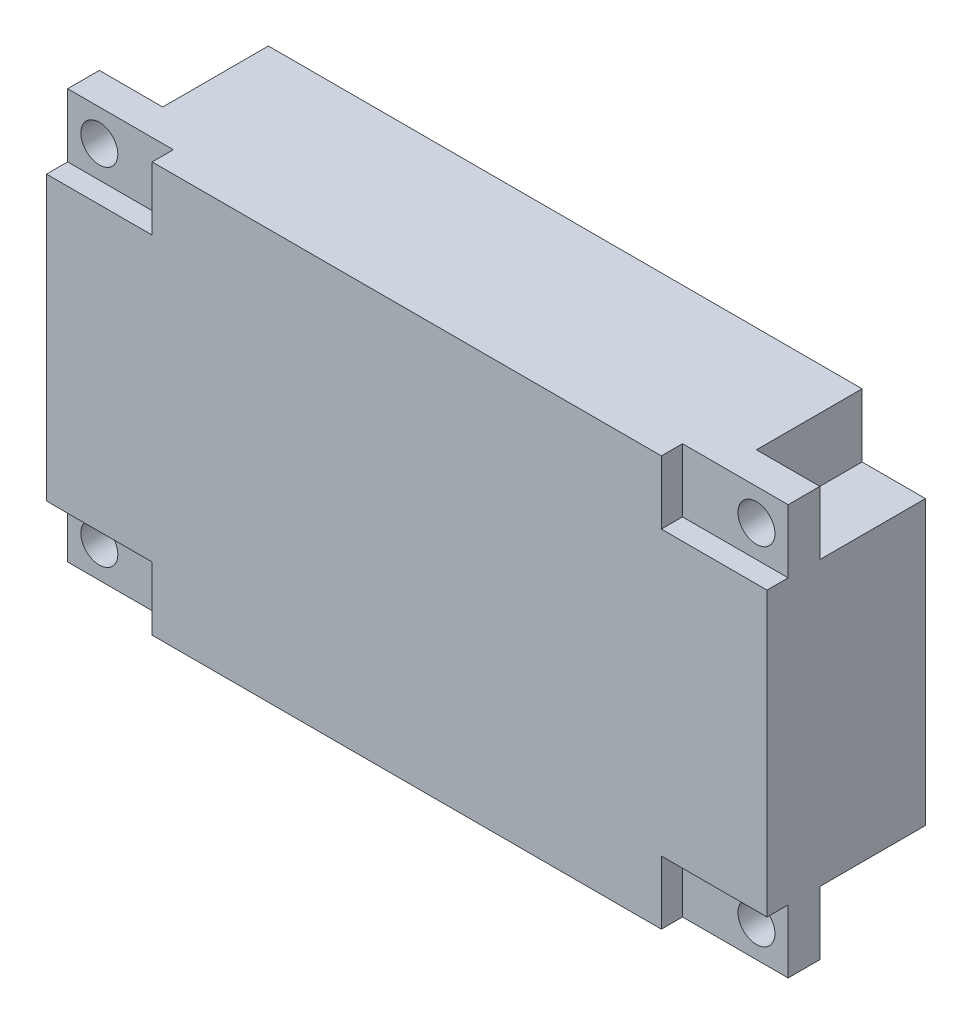
SolidWorks part; units mm, degrees
ref_plane "Plan de face" through (0, 0, 0) normal (0, 0, 1) x (1, 0, 0)
ref_plane "Plan de dessus" through (0, 0, 0) normal (0, 1, 0) x (1, 0, 0)
ref_plane "Plan de droite" through (0, 0, 0) normal (1, 0, 0) x (0, 0, -1)
sketch "Esquisse1" plane through (0, 0, 0) normal (0, 0, 1) x (1, 0, 0)
  line L1 (0, 0) -> (68.2, 0)
  line L2 (0, 0) -> (0, 38.8)
  line L3 (0, 38.8) -> (68.2, 38.8)
  line L4 (68.2, 0) -> (68.2, 38.8)
  dimension "D1" = 68.2
  dimension "D2" = 38.8
extrude "Boss.-Extru.2" add sketch "Esquisse1" along normal blind 15
sketch "Esquisse3" plane through (0, 0, 15) normal (0, 0, 1) x (1, 0, 0)
  line L0 (0, 38.8) -> (10, 38.8)
  line L1 (68.2, 38.8) -> (0, 38.8) construction
  line L2 (10, 38.8) -> (10, 32.8)
  line L3 (10, 32.8) -> (0, 32.8)
  line L4 (0, 38.8) -> (0, 0) construction
  line L5 (0, 32.8) -> (0, 38.8)
  line L6 (0, 0) -> (10, 0)
  line L7 (0, 0) -> (68.2, 0) construction
  line L8 (10, 0) -> (10, 6)
  line L9 (10, 6) -> (0, 6)
  line L10 (0, 6) -> (0, 0)
  line L11 (68.2, 0) -> (68.2, 6)
  line L12 (68.2, 0) -> (68.2, 38.8) construction
  line L13 (68.2, 6) -> (58.2, 6)
  line L14 (58.2, 6) -> (58.2, 0)
  line L15 (58.2, 0) -> (68.2, 0)
  line L16 (68.2, 38.8) -> (58.2, 38.8)
  line L17 (58.2, 38.8) -> (58.2, 32.8)
  line L18 (58.2, 32.8) -> (68.2, 32.8)
  line L19 (68.2, 32.8) -> (68.2, 38.8)
  dimension "D1" = 10
  dimension "D2" = 6
  dimension "D3" = 10
  dimension "D4" = 6
  dimension "D5" = 10
  dimension "D6" = 6
  dimension "D7" = 10
  dimension "D8" = 6
extrude "Enlèv. mat.-Extru.1" cut sketch "Esquisse3" against normal blind 2
sketch "Esquisse4" plane through (0, 0, 15) normal (0, 0, 1) x (1, 0, 0)
  line L0 (10, 38.8) -> (0, 38.8) construction
  line L1 (0, 38.8) -> (0, 32.8) construction
  line L2 (10, 6) -> (0, 6) construction
  line L3 (0, 6) -> (0, 0) construction
  line L4 (68.2, 6) -> (58.2, 6) construction
  line L6 (68.2, 0) -> (68.2, 6) construction
  line L7 (68.2, 38.8) -> (58.2, 38.8) construction
  line L8 (68.2, 32.8) -> (68.2, 38.8) construction
  circle A0 centre (3, 35.8) radius 1.75
  circle A1 centre (3, 3) radius 1.75
  circle A2 centre (65.2, 35.8) radius 1.75
  circle A3 centre (65.2, 3) radius 1.75
  dimension "D1" = 3.5
  dimension "D4" = 3.5
  dimension "D7" = 3.5
  dimension "D10" = 3.5
  dimension "D2" = 3
  dimension "D3" = 3
  dimension "D5" = 3
  dimension "D6" = 3
  dimension "D8" = 3
  dimension "D9" = 3
  dimension "D11" = 3
  dimension "D12" = 3
extrude "Enlèv. mat.-Extru.2" cut sketch "Esquisse4" against normal through all
sketch "Esquisse6" plane through (0, 0, 0) normal (0, 0, -1) x (-1, 0, 0)
  line L0 (-68.2, 38.8) -> (-62.2, 38.8)
  line L1 (-68.2, 38.8) -> (0, 38.8) construction
  line L2 (-62.2, 38.8) -> (-62.2, 32.8)
  line L3 (-62.2, 32.8) -> (-68.2, 32.8)
  line L4 (-68.2, 0) -> (-68.2, 38.8) construction
  line L5 (-68.2, 32.8) -> (-68.2, 38.8)
  line L6 (0, 38.8) -> (0, 32.8)
  line L7 (0, 38.8) -> (0, 0) construction
  line L8 (0, 32.8) -> (-6, 32.8)
  line L9 (-6, 32.8) -> (-6, 38.8)
  line L10 (-6, 38.8) -> (0, 38.8)
  line L11 (0, 0) -> (0, 6)
  line L12 (0, 6) -> (-6, 6)
  line L13 (-6, 6) -> (-6, 0)
  line L14 (0, 0) -> (-68.2, 0) construction
  line L15 (-6, 0) -> (0, 0)
  line L16 (-68.2, 0) -> (-62.2, 0)
  line L17 (-62.2, 0) -> (-62.2, 6)
  line L18 (-62.2, 6) -> (-68.2, 6)
  line L19 (-68.2, 6) -> (-68.2, 0)
  dimension "D1" = 6
  dimension "D2" = 6
  dimension "D3" = 6
  dimension "D4" = 6
  dimension "D5" = 6
  dimension "D6" = 6
  dimension "D7" = 6
  dimension "D8" = 6
extrude "Enlèv. mat.-Extru.3" cut sketch "Esquisse6" against normal blind 10
